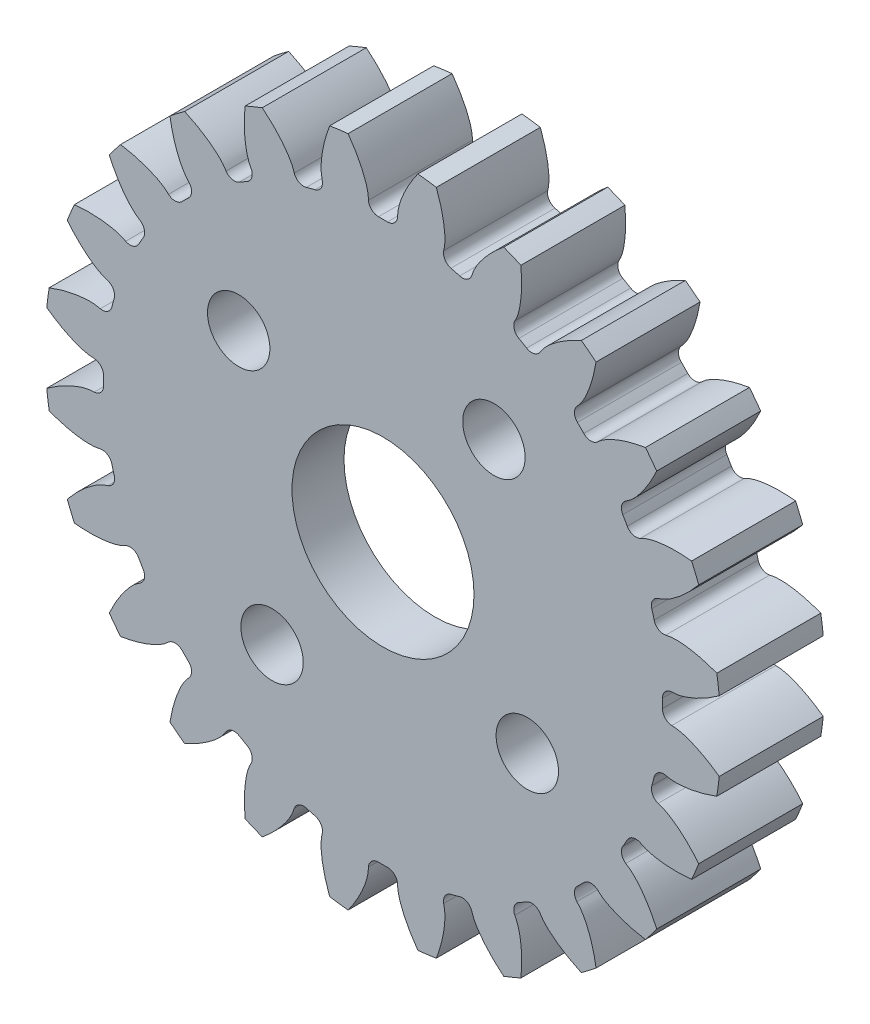
SolidWorks part; units mm, degrees
material "Vero PureWhite"
ref_plane "前视基准面" through (0, 0, 0) normal (0, 0, 1) x (1, 0, 0)
ref_plane "上视基准面" through (0, 0, 0) normal (0, 1, 0) x (1, 0, 0)
ref_plane "右视基准面" through (0, 0, 0) normal (1, 0, 0) x (0, 0, -1)
other "Configuration Table"
ref_axis "Axis1" through (0, 0, -88.99) along (0, 0, 1)
sketch "草图1" plane through (0, 0, 0) normal (0, 0, 1) x (1, 0, 0)
  circle A0 centre (0, 0) radius 13
extrude "LaShenA" add sketch "草图1" along normal blind 4
sketch "SketchA" plane through (0, 0, 4) normal (0, 0, 1) x (1, 0, 0)
  line L0 (0, 0) -> (0, 13) construction
  arc A0 (0.1732, 10.7486) -> (-0.1732, 10.7486) centre (0, 0) ccw
  arc A1 (1.7936, 13.4924) -> (-1.7936, 13.4924) centre (0, 0) ccw
  arc A2 (-0.1732, 10.7486) -> (-0.5586, 11.1053) centre (-0.1793, 11.1286) cw
  arc A3 (0.5586, 11.1053) -> (0.1732, 10.7486) centre (0.1793, 11.1286) cw
  circle A4 centre (0, 0) radius 11.2763 construction
  circle A5 centre (0, 0) radius 13 construction
  circle A6 centre (0, 0) radius 10.75 construction
  circle A7 centre (0, 0) radius 12 construction
  spline S0 degree 3 poles (0.5586, 11.1053) (0.5618, 11.1578) (0.5667, 11.2415) (0.5795, 11.3389) (0.5917, 11.3999) (0.6025, 11.4482) (0.6165, 11.5037) (0.6339, 11.5661) (0.6552, 11.6353) (0.6807, 11.7112) (0.7108, 11.7936) (0.7458, 11.8822) (0.786, 11.9769) (0.8319, 12.0775) (0.8838, 12.1837) (0.9418, 12.2952) (1.0065, 12.4119) (1.078, 12.5335) (1.1567, 12.6596) (1.2429, 12.79) (1.3368, 12.9243) (1.4386, 13.0623) (1.5886, 13.2548) (1.7092, 13.3975) (1.7936, 13.4924) knots 0.119767 0.119767 0.119767 0.119767 0.170317 0.200988 0.214489 0.230444 0.248855 0.26972 0.29304 0.318814 0.347044 0.377728 0.410866 0.44646 0.484508 0.525011 0.567969 0.613381 0.661248 0.71157 0.764347 0.819578 0.877264 1 1 1 1
  spline S1 degree 3 poles (-0.5586, 11.1053) (-0.5618, 11.1578) (-0.5667, 11.2415) (-0.5795, 11.3389) (-0.5917, 11.3999) (-0.6025, 11.4482) (-0.6165, 11.5037) (-0.6339, 11.5661) (-0.6552, 11.6353) (-0.6807, 11.7112) (-0.7108, 11.7936) (-0.7458, 11.8822) (-0.786, 11.9769) (-0.8319, 12.0775) (-0.8838, 12.1837) (-0.9418, 12.2952) (-1.0065, 12.4119) (-1.078, 12.5335) (-1.1567, 12.6596) (-1.2429, 12.79) (-1.3368, 12.9243) (-1.4386, 13.0623) (-1.5886, 13.2548) (-1.7092, 13.3975) (-1.7936, 13.4924) knots 0.119767 0.119767 0.119767 0.119767 0.170317 0.200988 0.214489 0.230444 0.248855 0.26972 0.29304 0.318814 0.347044 0.377728 0.410866 0.44646 0.484508 0.525011 0.567969 0.613381 0.661248 0.71157 0.764347 0.819578 0.877264 1 1 1 1
  dimension "D1" = 0.38
  dimension "Db" = 22.5526
  dimension "Da" = 26
  dimension "Df" = 21.5
  dimension "Dn" = 24
extrude "Cut-ExtrudeA" cut sketch "SketchA" against normal blind 30
pattern_circular "www.KYTool.cn" count 24 over 360 about axis through (0, 0, -88.99) along (0, 0, 1) of "Cut-ExtrudeA"
sketch "草图3" plane through (0, 0, 0) normal (0, 0, -1) x (-1, 0, 0)
  circle A0 centre (0, 0) radius 10.375 construction
  circle A1 centre (0, 0) radius 10.375
extrude "切除-拉伸2" cut sketch "草图3" against normal blind 2
hole_wizard "M2 间隙孔2" positions "草图7" profile "草图6" hole size "M2" standard "GB" end condition up to next
sketch "草图7" plane through (0, 0, 4) normal (0, 0, 1) x (1, 0, 0)
  line L3 (-5.5495, 4.2665) -> (-4.2665, -5.5495)
  line L4 (-4.2665, -5.5495) -> (5.5495, -4.2665)
  line L5 (5.5495, -4.2665) -> (4.2665, 5.5495)
  line L6 (4.2665, 5.5495) -> (-5.5495, 4.2665)
  circle A0 centre (0, 0) radius 7 construction
  point P0 (195.4366, 197.4945)
  point P1 (-5.5495, 4.2665)
  point P5 (4.2665, 5.5495)
  point P8 (-4.2665, -5.5495)
  point P11 (5.5495, -4.2665)
  dimension "D2" = 14
sketch "草图6" plane through (195.4366, 197.4945, 4) normal (1, 0, 0) x (0, -1, 0)
  line L0 (0, 0) -> (0, 4)
  line L1 (0, 4) -> (1.2, 4)
  line L2 (1.2, 4) -> (1.2, 0)
  line L5 (1.2, 0) -> (0, 0)
  line L11 (0, -6.35) -> (0, 107.95) construction
  dimension "通孔孔直径" = 2.4
  dimension "通孔孔深度" = 4
sketch "草图8" plane through (0, 0, 4) normal (0, 0, 1) x (1, 0, 0)
  circle A0 centre (0, 0) radius 3.5
  dimension "D1" = 7
extrude "切除-拉伸3" cut sketch "草图8" against normal up to next
